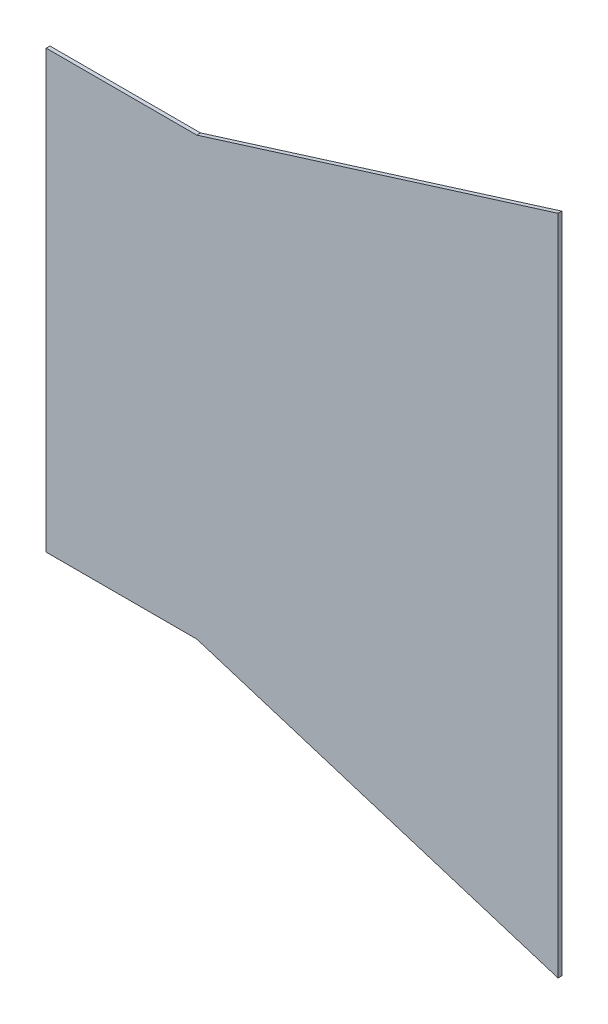
SolidWorks part; units mm, degrees
ref_plane "Front Plane" through (0, 0, 0) normal (1, 0, 0) x (0, 1, 0)
ref_plane "Top Plane" through (0, 0, 0) normal (0, 0, 1) x (0, 1, 0)
ref_plane "Right Plane" through (0, 0, 0) normal (0, 1, 0) x (-1, 0, 0)
sketch "Sketch1" plane through (0, 0, 0) normal (0, 0, 1) x (0, 1, 0)
  line L0 (-368.3, -127) -> (-368.3, 0)
  line L1 (-368.3, 0) -> (0, 0)
  line L2 (0, 0) -> (0, -127)
  line L3 (-368.3, -127) -> (-463.55, -431.8)
  line L4 (-463.55, -431.8) -> (95.25, -431.8)
  line L5 (95.25, -431.8) -> (0, -127)
  point P2 (-184.15, -431.8)
  point P7 (-184.15, 0)
  point P8 (0, 0)
  point P9 (-206.7741, 28.9379)
  point P10 (-391.9764, 87.8659)
  point P11 (0, 0)
  dimension "D1" = 368.3
  dimension "D2" = 127
  dimension "D3" = 558.8
  dimension "D4" = 304.8
extrude "Boss-Extrude1" add sketch "Sketch1" along normal blind 3.175
